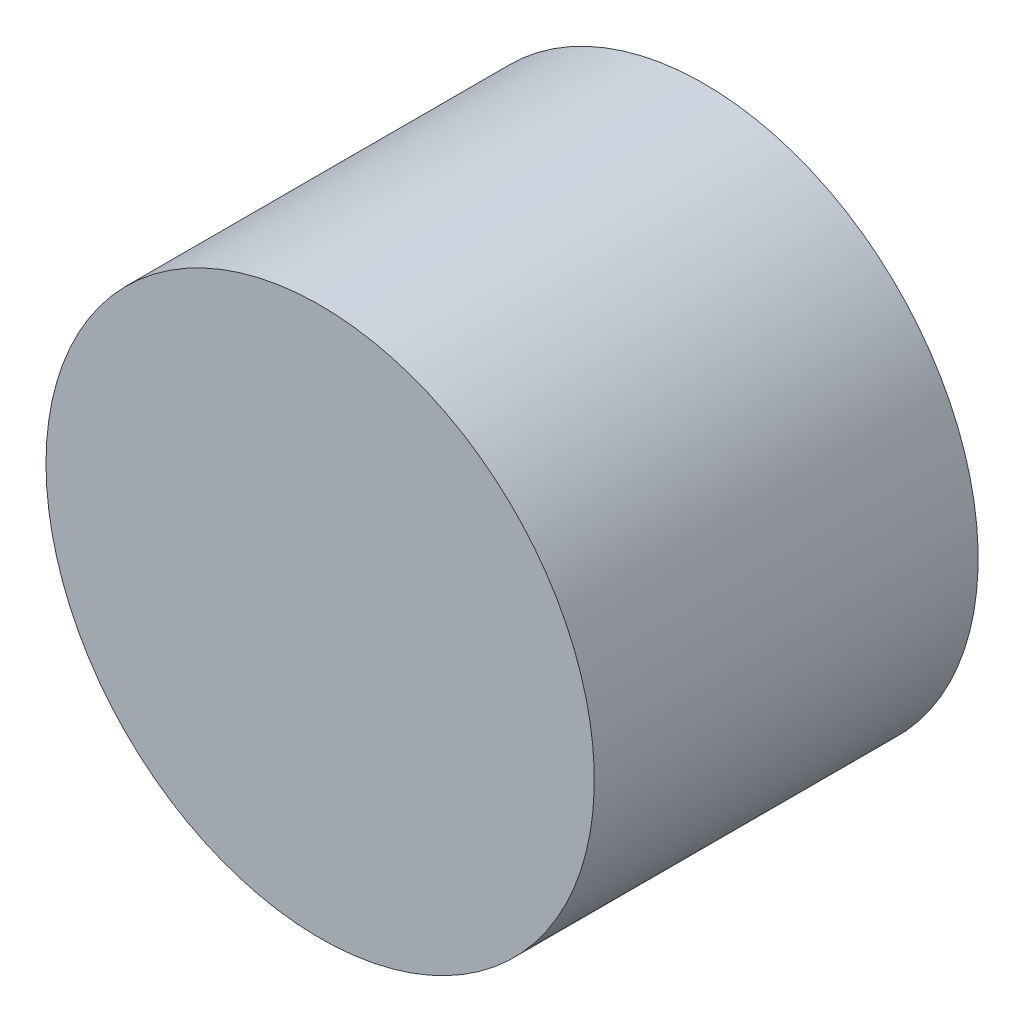
SolidWorks part; units mm, degrees
ref_plane "Alzado" through (0, 0, 0) normal (0, 0, 1) x (1, 0, 0)
ref_plane "Planta" through (0, 0, 0) normal (0, 1, 0) x (1, 0, 0)
ref_plane "Vista lateral" through (0, 0, 0) normal (1, 0, 0) x (0, 0, -1)
sketch "Croquis1" plane through (0, 0, 0) normal (0, 0, 1) x (1, 0, 0)
  circle A0 centre (0, 0) radius 15
extrude "Saliente-Extruir1" add sketch "Croquis1" along normal blind 21
sketch "Croquis2" plane through (0, 0, 0) normal (0, 0, -1) x (-1, 0, 0)
  circle A0 centre (0, 0) radius 2
extrude "Cortar-Extruir1" cut sketch "Croquis2" against normal blind 10
